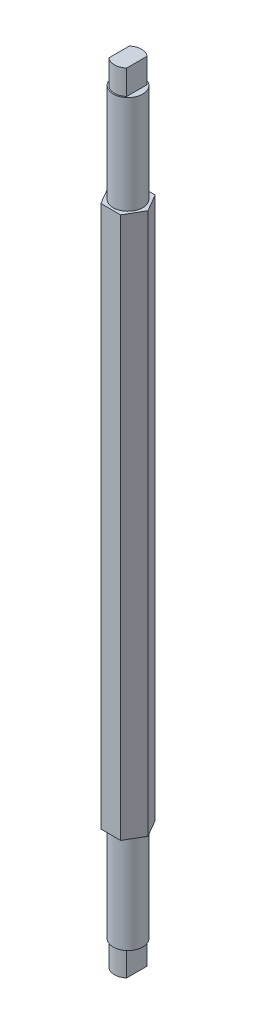
SolidWorks part; units mm, degrees
ref_plane "Front Plane" through (0, 0, 0) normal (0, 0, 1) x (1, 0, 0)
ref_plane "Top Plane" through (0, 0, 0) normal (0, 1, 0) x (1, 0, 0)
ref_plane "Right Plane" through (0, 0, 0) normal (1, 0, 0) x (0, 0, -1)
sketch "Çizim1" plane through (0, 0, 0) normal (0, 1, 0) x (1, 0, 0)
  line L1 (4.0415, 0) -> (2.0207, 3.5)
  line L2 (2.0207, 3.5) -> (-2.0207, 3.5)
  line L3 (-2.0207, 3.5) -> (-4.0415, 0)
  line L4 (-4.0415, 0) -> (-2.0207, -3.5)
  line L5 (-2.0207, -3.5) -> (2.0207, -3.5)
  line L6 (2.0207, -3.5) -> (4.0415, 0)
  circle A0 centre (0, 0) radius 3.5 construction
  dimension "D1" = 7
extrude "Yükseklik-Ekstrüzyon1" add sketch "Çizim1" along normal blind 110
sketch "Çizim2" plane through (0, 110, 0) normal (0, 1, 0) x (1, 0, 0)
  circle A0 centre (0, 0) radius 3
  dimension "D1" = 6
extrude "Yükseklik-Ekstrüzyon2" add sketch "Çizim2" along normal blind 20
sketch "Çizim3" plane through (0, 130, 0) normal (0, 1, 0) x (1, 0, 0)
  line L0 (-1.7989, 2.08) -> (-1.7989, -2.08)
  line L1 (1.7989, 2.08) -> (1.7989, -2.08)
  circle A0 centre (0, 0) radius 2.75
  dimension "D1" = 5.5
  dimension "D2" = 4.16
  dimension "D3" = 4.16
extrude "Yükseklik-Ekstrüzyon3" add sketch "Çizim3" along normal blind 5 contours L1 A0 L0
sketch "Çizim4" plane through (0, 0, 0) normal (0, -1, 0) x (1, 0, 0)
  circle A0 centre (0, 0) radius 3
  dimension "D1" = 6
extrude "Yükseklik-Ekstrüzyon4" add sketch "Çizim4" along normal blind 20
sketch "Çizim5" plane through (0, -20, 0) normal (0, -1, 0) x (1, 0, 0)
  line L0 (-1.7989, 2.08) -> (-1.7989, -2.08)
  line L1 (1.7989, 2.08) -> (1.7989, -2.08)
  circle A0 centre (0, 0) radius 2.75
  dimension "D1" = 5.5
  dimension "D2" = 4.16
  dimension "D3" = 4.16
extrude "Yükseklik-Ekstrüzyon5" add sketch "Çizim5" along normal blind 5 contours L1 A0 L0
